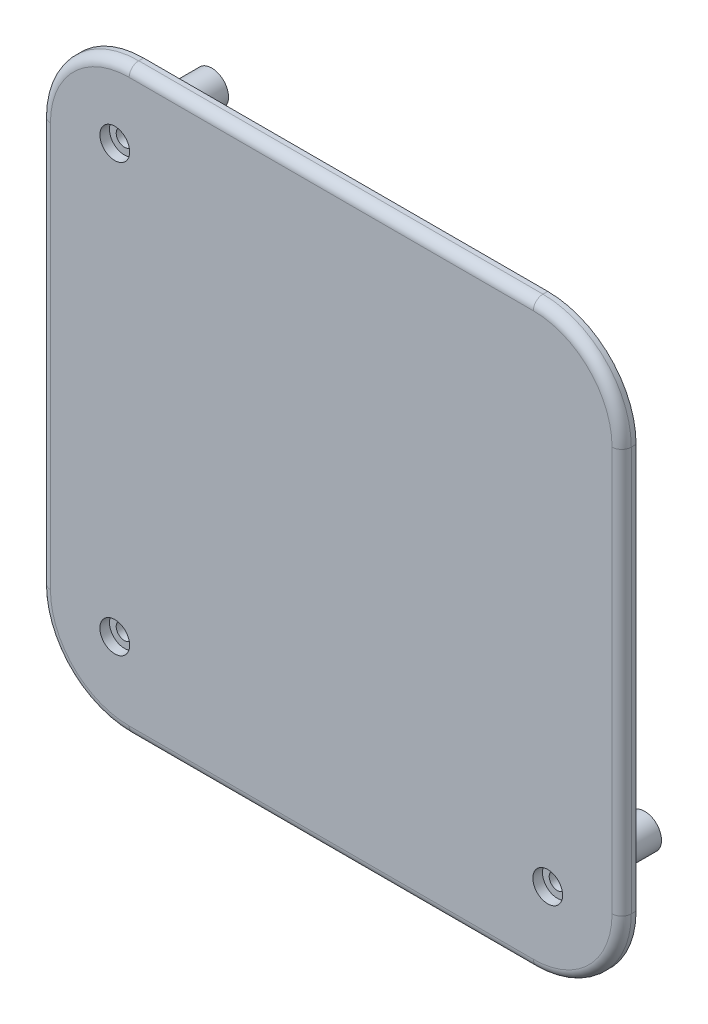
SolidWorks part; units mm, degrees
ref_plane "前视基准面" through (0, 0, 0) normal (0, 0, 1) x (1, 0, 0)
ref_plane "上视基准面" through (0, 0, 0) normal (0, 1, 0) x (1, 0, 0)
ref_plane "右视基准面" through (0, 0, 0) normal (1, 0, 0) x (0, 0, -1)
sketch "草图1" plane through (0, 0, 0) normal (0, 0, 1) x (1, 0, 0)
  line L1 (-26.273, 44.2869) -> (15.827, 44.2869)
  line L2 (-35.473, 35.0869) -> (-35.473, -7.0131)
  line L3 (-26.273, -16.2131) -> (15.827, -16.2131)
  line L4 (25.027, 35.0869) -> (25.027, -7.0131)
  arc A0 (-26.273, -16.2131) -> (-35.473, -7.0131) centre (-26.273, -7.0131) cw
  arc A1 (-35.473, 35.0869) -> (-26.273, 44.2869) centre (-26.273, 35.0869) cw
  arc A2 (15.827, 44.2869) -> (25.027, 35.0869) centre (15.827, 35.0869) cw
  arc A3 (25.027, -7.0131) -> (15.827, -16.2131) centre (15.827, -7.0131) cw
  point P6 (-35.473, -16.2131)
  point P11 (25.027, 44.2869)
  point P14 (25.027, -16.2131)
  dimension "D3" = 9.2
  dimension "D1" = 60.5
  dimension "D2" = 60.5
extrude "凸台-拉伸1" add sketch "草图1" along normal blind 1.5
sketch "草图2" plane through (0, 0, 1.5) normal (0, 0, 1) x (1, 0, 0)
  line L0 (15.827, 44.2869) -> (-26.273, 44.2869) construction
  line L1 (-35.473, 35.0869) -> (-35.473, -7.0131) construction
  circle A0 centre (-27.773, 36.5869) radius 0.85
  dimension "D1" = 1.7
  dimension "D2" = 7.7
  dimension "D3" = 7.7
extrude "切除-拉伸1" cut sketch "草图2" against normal blind 11
sketch "草图4" plane through (0, 0, 1.5) normal (0, 0, 1) x (1, 0, 0)
  line L0 (-26.273, -16.2131) -> (15.827, -16.2131) construction
  line L1 (-35.473, 35.0869) -> (-35.473, -7.0131) construction
  circle A0 centre (-27.773, -7.9131) radius 0.85
  dimension "D1" = 1.7
  dimension "D2" = 8.3
  dimension "D3" = 7.7
extrude "切除-拉伸2" cut sketch "草图4" against normal blind 11.5
sketch "草图5" plane through (0, 0, 1.5) normal (0, 0, 1) x (1, 0, 0)
  line L0 (-26.273, -16.2131) -> (15.827, -16.2131) construction
  line L1 (25.027, -7.0131) -> (25.027, 35.0869) construction
  circle A0 centre (17.327, -7.9131) radius 0.85
  dimension "D1" = 1.7
  dimension "D2" = 8.3
  dimension "D3" = 7.7
extrude "切除-拉伸3" cut sketch "草图5" against normal blind 11.5
sketch "草图8" plane through (0, 0, 0) normal (0, 0, -1) x (-1, 0, 0)
  circle A0 centre (27.773, 36.5869) radius 0.85
  circle A1 centre (27.773, 36.5869) radius 1.75
  circle A2 centre (27.773, -7.9131) radius 0.85
  circle A3 centre (27.773, -7.9131) radius 1.75
  circle A4 centre (-17.327, -7.9131) radius 0.85
  circle A5 centre (-17.327, -7.9131) radius 1.75
  dimension "D1" = 3.5
  dimension "D2" = 3.5
  dimension "D3" = 3.5
sketch "草图9" plane through (0, 0, 1.5) normal (0, 0, 1) x (1, 0, 0)
  circle A0 centre (-27.773, 36.5869) radius 0.85
  circle A1 centre (-27.773, 36.5869) radius 1.55
  circle A2 centre (-27.773, -7.9131) radius 0.85
  circle A3 centre (-27.773, -7.9131) radius 1.55
  circle A4 centre (17.327, -7.9131) radius 0.85
  circle A5 centre (17.327, -7.9131) radius 1.55
  dimension "D1" = 3.1
  dimension "D2" = 3.1
  dimension "D3" = 3.1
extrude "切除-拉伸5" cut sketch "草图9" against normal blind 1
extrude "凸台-拉伸6" add sketch "草图8" along normal blind 8.6
fillet "圆角2" radius 1 8 edges at (-35.473, 14.0369, 1.5) (-32.7784, 41.5923, 1.5) (-5.223, 44.2869, 1.5) (22.3324, 41.5923, 1.5) (25.027, 14.0369, 1.5) (22.3324, -13.5185, 1.5) (-5.223, -16.2131, 1.5) (-32.7784, -13.5185, 1.5)
